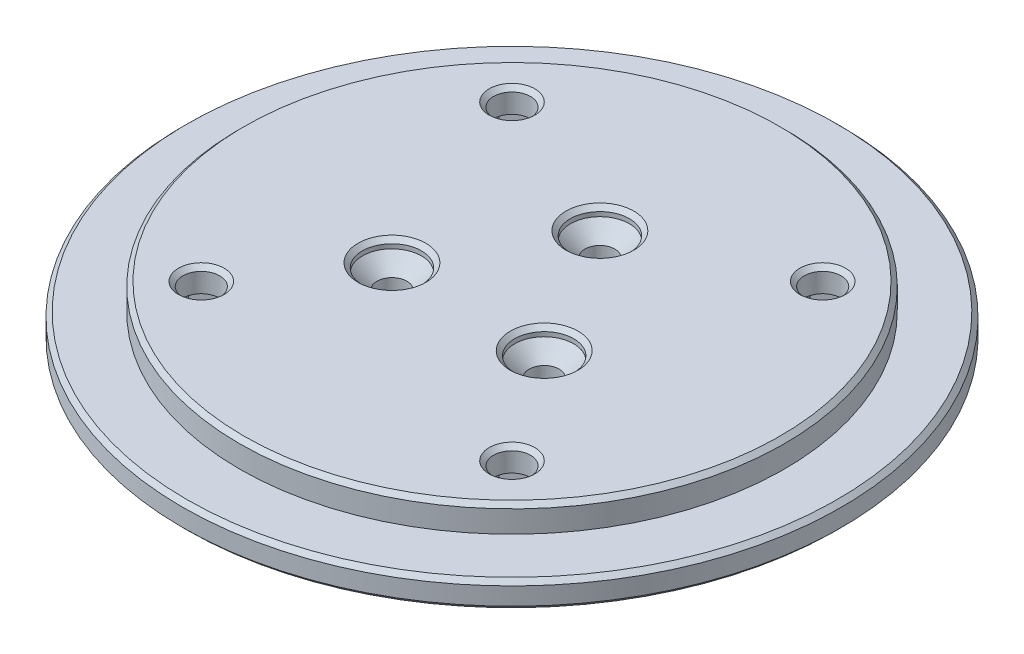
SolidWorks part; units mm, degrees
ref_plane "Front Plane" through (0, 0, 0) normal (0, 0, 1) x (1, 0, 0)
ref_plane "Top Plane" through (0, 0, 0) normal (0, 1, 0) x (1, 0, 0)
ref_plane "Right Plane" through (0, 0, 0) normal (1, 0, 0) x (0, 0, -1)
sketch "Sketch1" plane through (0, 0, 0) normal (0, 1, 0) x (1, 0, 0)
  circle A0 centre (0, 0) radius 37.5
  dimension "D1" = 75
extrude "Boss-Extrude1" add sketch "Sketch1" along normal blind 6
hole_wizard "CSK for M3 SFHCS1" positions "Sketch2" profile "Sketch3" countersink size "M3" standard "ANSI Metric"
sketch "Sketch2" plane through (0, 6, 0) normal (0, 1, 0) x (1, 0, 0)
  line L0 (-8.66, -4.9999) -> (0, 9.9997) construction
  line L1 (0, 9.9997) -> (8.66, -4.9999) construction
  line L2 (8.66, -4.9999) -> (-8.66, -4.9999) construction
  circle A0 centre (0, 0) radius 9.9997
  point P5 (0, 9.9997)
  point P7 (-8.66, -4.9999)
  point P9 (8.66, -4.9999)
  dimension "D1" = 17.32
sketch "Sketch3" plane through (8.66, 6, 4.9999) normal (1, 0, 0) x (0, 0, 1)
  line L0 (0, 0) -> (0, 11.0215)
  line L1 (0, 11.0215) -> (1.7, 10)
  line L2 (1.7, 10) -> (1.7, 2.66)
  line L3 (1.7, 2.66) -> (3.36, 1)
  line L4 (3.36, 1) -> (3.36, 0)
  line L6 (3.36, 0) -> (0, 0)
  line L7 (-1.7, 2.66) -> (-3.36, 1) construction
  line L10 (0, 11.0215) -> (-1.7, 10) construction
  line L11 (0, -6.35) -> (0, 107.95) construction
  dimension "Hole Dia." = 3.4
  dimension "Hole Depth" = 10
  dimension "C'Sink Dia." = 6.72
  dimension "C'Sink Angle" = 90
  dimension "Drill Angle" = 118
  dimension "Head Clearance" = 1
sketch "Sketch5" plane through (0, 6, 0) normal (0, 1, 0) x (1, 0, 0)
  circle A0 centre (0, 0) radius 31
  dimension "D1" = 62
extrude "Cut-Extrude2" cut sketch "Sketch5" against normal blind 3 flip side to cut
hole_wizard "Ø4.0mm Dowel Hole1" positions "Sketch6" profile "Sketch7" hole size "Ø4.0" standard "ANSI Metric"
sketch "Sketch6" plane through (0, 6, 0) normal (0, 1, 0) x (1, 0, 0)
  line L1 (-17.6777, 17.6777) -> (17.6777, 17.6777)
  line L2 (-17.6777, 17.6777) -> (-17.6777, -17.6777)
  line L3 (-17.6777, -17.6777) -> (17.6777, -17.6777)
  line L4 (17.6777, 17.6777) -> (17.6777, -17.6777)
  circle A0 centre (0, 0) radius 25
  point P5 (-17.6777, 17.6777)
  point P6 (17.6777, -17.6777)
  point P97 (-17.6777, -17.6777)
  point P98 (17.6777, 17.6777)
  dimension "D1" = 50
sketch "Sketch7" plane through (17.6777, 6, -17.6777) normal (1, 0, 0) x (0, 0, 1)
  line L0 (0, 0) -> (0, 11.2618)
  line L1 (0, 11.2618) -> (2.1, 10)
  line L2 (2.1, 10) -> (2.1, 0)
  line L5 (2.1, 0) -> (0, 0)
  line L10 (0, 11.2618) -> (-2.1, 10) construction
  line L11 (0, -6.35) -> (0, 107.95) construction
  dimension "Hole Dia." = 4.2
  dimension "Hole Depth" = 10
  dimension "Drill Angle" = 118
sketch "Sketch8" plane through (0, 0, 0) normal (0, -1, 0) x (1, 0, 0)
  line L1 (-14.2277, 15.6858) -> (-14.2277, 19.6695)
  line L2 (-14.2277, 19.6695) -> (-17.6777, 21.6614)
  line L3 (-17.6777, 21.6614) -> (-21.1277, 19.6695)
  line L4 (-21.1277, 19.6695) -> (-21.1277, 15.6858)
  line L5 (-21.1277, 15.6858) -> (-17.6777, 13.694)
  line L6 (-17.6777, 13.694) -> (-14.2277, 15.6858)
  line L7 (17.6777, 13.694) -> (21.1277, 15.6858)
  line L8 (21.1277, 15.6858) -> (21.1277, 19.6695)
  line L9 (21.1277, 19.6695) -> (17.6777, 21.6614)
  line L10 (17.6777, 21.6614) -> (14.2277, 19.6695)
  line L11 (14.2277, 19.6695) -> (14.2277, 15.6858)
  line L12 (14.2277, 15.6858) -> (17.6777, 13.694)
  line L13 (14.2277, -19.6695) -> (17.6777, -21.6614)
  line L14 (17.6777, -21.6614) -> (21.1277, -19.6695)
  line L15 (21.1277, -19.6695) -> (21.1277, -15.6858)
  line L16 (21.1277, -15.6858) -> (17.6777, -13.694)
  line L17 (17.6777, -13.694) -> (14.2277, -15.6858)
  line L18 (14.2277, -15.6858) -> (14.2277, -19.6695)
  line L19 (-14.2277, -19.6695) -> (-14.2277, -15.6858)
  line L20 (-14.2277, -15.6858) -> (-17.6777, -13.694)
  line L21 (-17.6777, -13.694) -> (-21.1277, -15.6858)
  line L22 (-21.1277, -15.6858) -> (-21.1277, -19.6695)
  line L23 (-21.1277, -19.6695) -> (-17.6777, -21.6614)
  line L24 (-17.6777, -21.6614) -> (-14.2277, -19.6695)
  circle A0 centre (-17.6777, 17.6777) radius 3.45 construction
  circle A1 centre (17.6777, 17.6777) radius 3.45 construction
  circle A2 centre (17.6777, -17.6777) radius 3.45 construction
  circle A3 centre (-17.6777, -17.6777) radius 3.45 construction
  dimension "D1" = 6.9
extrude "Cut-Extrude3" cut sketch "Sketch8" against normal blind 3.3
chamfer "Chamfer1" distance 0.5 angle 45 37 edges at (0, 0, 37.5) (8.66, 0, 6.6999) (-8.66, 0, 6.6999) (0, 0, -8.2997) (-15.9527, 0, 20.6655) (-19.4027, 0, 20.6655) (-21.1277, 0, 17.6777) (-19.4027, 0, 14.6899) (-15.9527, 0, 14.6899) (-14.2277, 0, 17.6777) (21.1277, 0, 17.6777) (19.4027, 0, 20.6655) (15.9527, 0, 20.6655) (14.2277, 0, 17.6777) (15.9527, 0, 14.6899) (19.4027, 0, 14.6899) (19.4027, 0, -20.6655) (21.1277, 0, -17.6777) (19.4027, 0, -14.6899) (15.9527, 0, -14.6899) (14.2277, 0, -17.6777) (15.9527, 0, -20.6655) (-15.9527, 0, -14.6899) (-19.4027, 0, -14.6899) (-21.1277, 0, -17.6777) (-19.4027, 0, -20.6655) (-15.9527, 0, -20.6655) (-14.2277, 0, -17.6777) (0, 6, 31) (0, 6, -6.6397) (-8.66, 6, 8.3599) (8.66, 6, 8.3599) (17.6777, 6, -15.5777) (-17.6777, 6, 19.7777) (17.6777, 6, 19.7777) (-17.6777, 6, -15.5777) (0, 3, 37.5)
